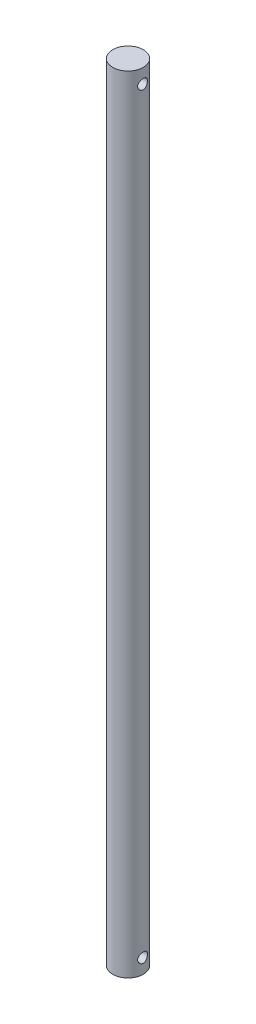
SolidWorks part; units mm, degrees
ref_plane "Front Plane" through (0, 0, 0) normal (0, 0, 1) x (1, 0, 0)
ref_plane "Top Plane" through (0, 0, 0) normal (0, 1, 0) x (1, 0, 0)
ref_plane "Right Plane" through (0, 0, 0) normal (1, 0, 0) x (0, 0, -1)
sketch "Sketch1" plane through (0, 0, 0) normal (0, 1, 0) x (1, 0, 0)
  circle A0 centre (0, 0) radius 9.906
  dimension "D1" = 19.812
extrude "Boss-Extrude1" add sketch "Sketch1" along normal blind 508
sketch "Sketch2" plane through (0, 0, 0) normal (1, 0, 0) x (0, 0, -1)
  line L0 (9.906, 508) -> (-9.906, 508) construction
  line L6 (-9.906, 508) -> (-9.906, 0) construction
  circle A0 centre (0, 498.602) radius 3.175
  dimension "D2" = 6.35
  dimension "D1" = 9.398
  dimension "D3" = 9.906
extrude "Cut-Extrude1" cut sketch "Sketch2" against normal blind 22.86 from offset 20.32
ref_plane "Plane1" through (0, 254, 0) normal (0, 1, 0) x (1, 0, 0)
mirror "Mirror1" about plane through (0, 254, 0) normal (0, 1, 0) of "Cut-Extrude1"
